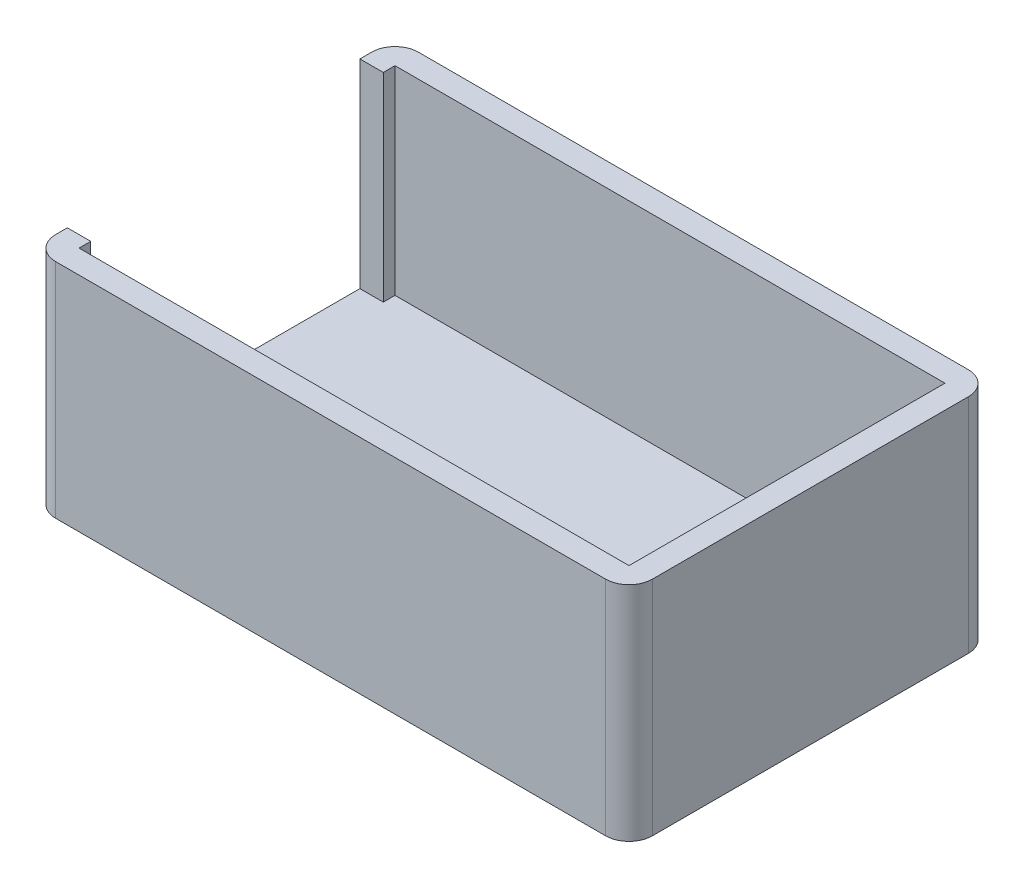
SolidWorks part; units mm, degrees
ref_plane "Front Plane" through (0, 0, 0) normal (0, 0, 1) x (1, 0, 0)
ref_plane "Top Plane" through (0, 0, 0) normal (0, 1, 0) x (1, 0, 0)
ref_plane "Right Plane" through (0, 0, 0) normal (1, 0, 0) x (0, 0, -1)
sketch "Sketch1" plane through (0, 0, 0) normal (0, 1, 0) x (1, 0, 0)
  line L1 (0, 0) -> (51, 0)
  line L2 (0, 0) -> (0, 31)
  line L3 (0, 31) -> (51, 31)
  line L4 (51, 0) -> (51, 31)
  dimension "D1" = 31
  dimension "D2" = 51
extrude "Boss-Extrude1" add sketch "Sketch1" along normal blind 2
sketch "Sketch2" plane through (0, 2, 0) normal (0, 1, 0) x (1, 0, 0)
  line L0 (51, 0) -> (51, 31) construction
  line L1 (0, 0) -> (49, 0)
  line L2 (0, 0) -> (0, 2)
  line L3 (0, 2) -> (49, 2)
  line L4 (49, 0) -> (49, 2)
  line L7 (51, 31) -> (49, 31)
  line L8 (51, 31) -> (51, 0)
  line L9 (51, 0) -> (49, 0)
  line L10 (49, 31) -> (49, 0)
  line L11 (0, 31) -> (49, 31)
  line L12 (0, 31) -> (0, 29)
  line L13 (0, 29) -> (49, 29)
  line L14 (49, 31) -> (49, 29)
  line L15 (0, 2) -> (2, 2)
  line L16 (0, 2) -> (0, 3)
  line L17 (0, 3) -> (2, 3)
  line L18 (2, 2) -> (2, 3)
  line L19 (0, 29) -> (2, 29)
  line L20 (0, 29) -> (0, 28)
  line L21 (0, 28) -> (2, 28)
  line L22 (2, 29) -> (2, 28)
  line M11 (0, 31) -> (0, 0)
  line M12 (0, 0) -> (51, 0)
  line M13 (51, 0) -> (51, 31)
  line M14 (51, 31) -> (0, 31)
  dimension "D1" = 2
  dimension "D2" = 2
  dimension "D3" = 2
  dimension "D4" = 49
  dimension "D5" = 2
  dimension "D6" = 2
  dimension "D7" = 1
  dimension "D8" = 2
  dimension "D9" = 1
extrude "Boss-Extrude2" add sketch "Sketch2" along normal blind 17 contours L10 L4 M14 M12 M13 | L4 L3 M12 M11 | L13 L10 M11 M14 | L20 L19 L22 L21 | L16 L15 L18 L17
fillet "Fillet3" radius 2 1 edges at (51, 9.5, 0)
fillet "Fillet4" radius 2 1 edges at (51, 9.5, -31)
fillet "Fillet5" radius 2 1 edges at (0, 9.5, 0)
fillet "Fillet6" radius 2 1 edges at (0, 9.5, -31)
